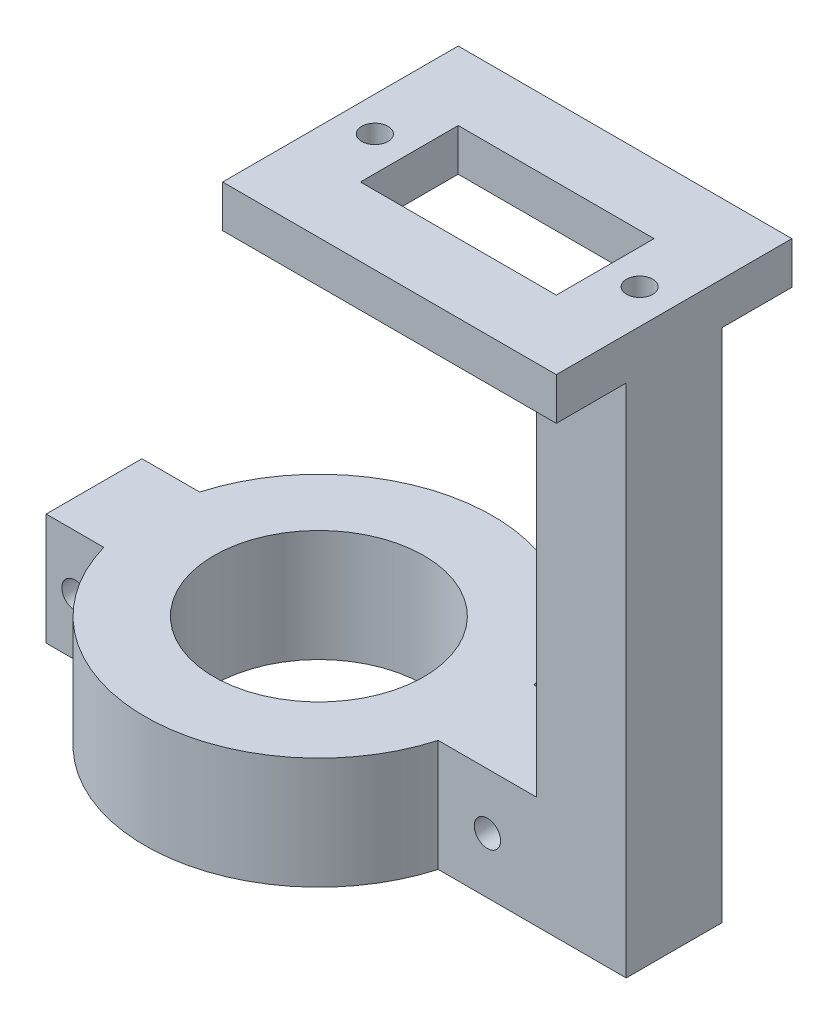
SolidWorks part; units mm, degrees
ref_plane "前基準面" through (0, 0, 0) normal (0, 0, 1) x (1, 0, 0)
ref_plane "上基準面" through (0, 0, 0) normal (0, 1, 0) x (1, 0, 0)
ref_plane "右基準面" through (0, 0, 0) normal (1, 0, 0) x (0, 0, -1)
sketch "草圖1" plane through (0, 0, 0) normal (0, 1, 0) x (1, 0, 0)
  line L1 (-14.225, 7.1) -> (14.225, 7.1)
  line L2 (-14.225, 7.1) -> (-14.225, -7.1)
  line L3 (-14.225, -7.1) -> (14.225, -7.1)
  line L4 (14.225, 7.1) -> (14.225, -7.1)
  line L5 (-14.225, 7.1) -> (14.225, -7.1) construction
  line L6 (-14.225, -7.1) -> (14.225, 7.1) construction
  point P0 (0, 0)
  dimension "D1" = 14.2
  dimension "D2" = 28.45
extrude "伸長-薄件1" add sketch "草圖1" along normal blind 12.25 thin thin type one direction wall 10
sketch "草圖2" plane through (0, 12.25, 0) normal (0, 1, 0) x (1, 0, 0)
  line L0 (-1014.255, 0) -> (48985.745, 0) construction
  line L1 (-14.225, 7.1) -> (-14.225, -7.1) construction
  line L2 (-19.225, -988.4004) -> (-19.225, 49011.5996) construction
  line L3 (-24.225, 17.1) -> (-19.225, 17.1) construction
  line L4 (-24.225, 17.1) -> (-24.225, 11.5996) construction
  line L5 (-24.225, 11.5996) -> (-19.225, 11.5996) construction
  line L6 (-19.225, 17.1) -> (-19.225, 11.5996) construction
  line L7 (24.225, 17.1) -> (19.225, 17.1) construction
  line L8 (24.225, 17.1) -> (24.225, 12.4477) construction
  line L9 (24.225, 12.4477) -> (19.225, 12.4477) construction
  line L10 (19.225, 17.1) -> (19.225, 12.4477) construction
  line L11 (19.225, -987.5523) -> (19.225, 49012.4477) construction
  circle A0 centre (-19.225, 0) radius 1.91
  circle A1 centre (19.225, 0) radius 1.91
  point P5 (-14.225, 0)
  dimension "D3" = 3.82
  dimension "D4" = 3.82
  dimension "D1" = 5
  dimension "D2" = 5
extrude "除料-伸長1" cut sketch "草圖2" against normal through all
sketch "草圖4" plane through (0, 0, 0) normal (0, -1, 0) x (1, 0, 0)
  line L0 (-1000, 0) -> (49000, 0) construction
  line L1 (24.225, 17.1) -> (24.225, -17.1) construction
  line L2 (11.225, 6.955) -> (24.225, 6.955)
  line L3 (11.225, 6.955) -> (11.225, -6.955)
  line L4 (11.225, -6.955) -> (24.225, -6.955)
  line L5 (24.225, 6.955) -> (24.225, -6.955)
  line L6 (11.225, 6.955) -> (24.225, -6.955) construction
  line L7 (11.225, -6.955) -> (24.225, 6.955) construction
  point P1 (17.725, 0)
  dimension "D1" = 13.91
  dimension "D2" = 13
extrude "填料-伸長1" add sketch "草圖4" along normal blind 74.82
sketch "草圖5" plane through (11.225, 0, 0) normal (-1, 0, 0) x (0, 0, 1)
  line L0 (6.955, -74.82) -> (6.955, 0) construction
  line L1 (-6.955, -74.82) -> (6.955, -74.82)
  line L2 (-6.955, -74.82) -> (-6.955, -58.59)
  line L3 (-6.955, -58.59) -> (6.955, -58.59)
  line L4 (6.955, -74.82) -> (6.955, -58.59)
  dimension "D1" = 16.23
extrude "填料-伸長2" add sketch "草圖5" along normal blind 16
sketch "草圖7" plane through (3.6267, -74.82, 0) normal (0, -1, 0) x (1, 0, 0)
  circle A0 centre (-30.9782, 0) radius 15.25
  dimension "D1" = 30.5
extrude "伸長-薄件2" add sketch "草圖7" against normal blind 16.23 thin
ref_plane "平面1" through (-60, 0, 0) normal (1, 0, 0) x (0, 0, -1)
ref_plane "平面2" through (-55, 0, 0) normal (1, 0, 0) x (0, 0, -1)
ref_plane "平面3" through (-60, 0, 0) normal (1, 0, 0) x (0, 0, -1)
sketch "草圖15" plane through (0, 0, -6.955) normal (0, 0, -1) x (-1, 0, 0)
  line L0 (-996.9218, -66.705) -> (49003.0782, -66.705) construction
  line L1 (3.0782, -74.82) -> (3.0782, -58.59) construction
  line L2 (-4.0734, -1058.59) -> (-4.0734, 48941.41) construction
  line L3 (3.0782, -58.59) -> (-11.225, -58.59) construction
  circle A0 centre (-4.0734, -66.705) radius 1.91
  point P5 (3.0782, -66.705)
  point P10 (-4.0734, -58.59)
  dimension "D1" = 3.82
extrude "除料-伸長6" cut sketch "草圖15" against normal through all
ref_plane "平面4" through (-60, 0, 0) normal (1, 0, 0) x (0, 0, -1)
sketch "草圖16" plane through (-60, 0, 0) normal (1, 0, 0) x (0, 0, -1)
  line L1 (6.955, -58.59) -> (-6.955, -58.59)
  line L2 (6.955, -58.59) -> (6.955, -74.82)
  line L3 (6.955, -74.82) -> (-6.955, -74.82)
  line L4 (-6.955, -58.59) -> (-6.955, -74.82)
extrude "填料-伸長4" add sketch "草圖16" along normal blind 10
sketch "草圖17" plane through (0, 0, -6.955) normal (0, 0, -1) x (-1, 0, 0)
  line L0 (-948.3753, -66.705) -> (49051.6247, -66.705) construction
  line L1 (51.6247, -74.82) -> (51.6247, -58.59) construction
  line L2 (55.8124, -1058.59) -> (55.8124, 48941.41) construction
  line L3 (51.6247, -58.59) -> (60, -58.59) construction
  circle A0 centre (55.8124, -66.705) radius 1.91
  point P5 (51.6247, -66.705)
  point P10 (55.8124, -58.59)
  dimension "D1" = 3.82
extrude "除料-伸長7" cut sketch "草圖17" against normal through all
sketch "草圖18" plane through (0, 0, -17.1) normal (0, 0, -1) x (-1, 0, 0)
  line L0 (-1024.225, 6.125) -> (48975.775, 6.125) construction
  line L1 (-24.225, 12.25) -> (-24.225, 0) construction
  line L3 (-24.2045, 6.125) -> (24.225, 6.125)
  line L4 (-24.2045, 6.125) -> (-24.2045, 12.25)
  line L5 (-24.2045, 12.25) -> (24.225, 12.25)
  line L6 (24.225, 6.125) -> (24.225, 12.25)
  point P5 (-24.225, 6.125)
extrude "除料-伸長8" cut sketch "草圖18" against normal through all
sketch "草圖19" plane through (24.2045, 0, 0) normal (-1, 0, 0) x (0, 0, 1)
  line L1 (-17.1, 6.125) -> (17.1, 6.125)
  line L2 (-17.1, 6.125) -> (-17.1, 12.25)
  line L3 (-17.1, 12.25) -> (17.1, 12.25)
  line L4 (17.1, 6.125) -> (17.1, 12.25)
extrude "除料-伸長9" cut sketch "草圖19" against normal blind 10
